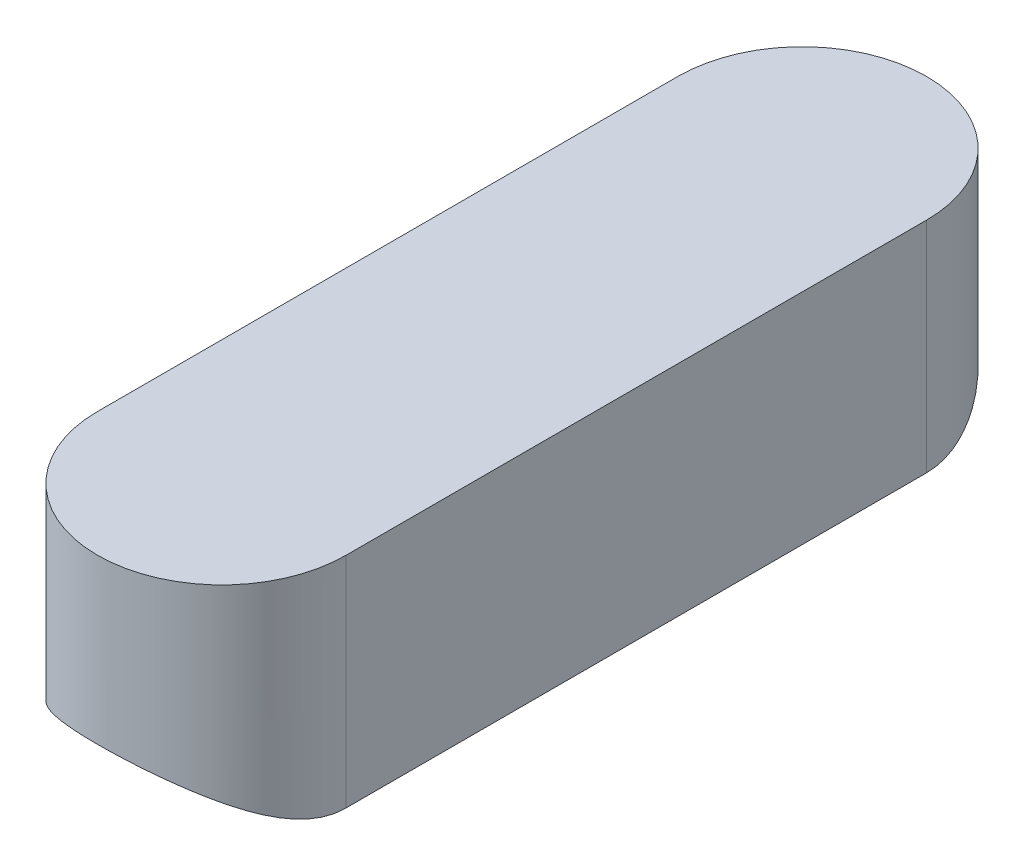
SolidWorks part; units mm, degrees
material "Polyetheretherketone (PEEK)"
ref_plane "Front Plane" through (0, 0, 0) normal (0, 0, 1) x (1, 0, 0)
ref_plane "Top Plane" through (0, 0, 0) normal (0, 1, 0) x (1, 0, 0)
ref_plane "Right Plane" through (0, 0, 0) normal (1, 0, 0) x (0, 0, -1)
sketch "Sketch1" plane through (0, 0, 0) normal (0, 0, 1) x (1, 0, 0)
  line L2 (3, 2.7208) -> (3, 8)
  line L3 (3, 8) -> (-3, 8)
  line L4 (-3, 2.7208) -> (-3, 8)
  line L5 (0, 0) -> (-3, 8) construction
  line L6 (3, 8) -> (0, 0) construction
  arc A0 (3, 2.7208) -> (-3, 2.7208) centre (0, 0) ccw
  dimension "D1" = 4.05
  dimension "D2" = 6
  dimension "D3" = 8
  dimension "D4" = 3
extrude "Boss-Extrude1" add sketch "Sketch1" along normal blind 20
sketch "Sketch2" plane through (0, 8, 0) normal (0, 1, 0) x (1, 0, 0)
  line L0 (0, 0) -> (0, -21.0822) construction
  line L1 (3, -20) -> (-3, -20) construction
  line L2 (-3, -3) -> (-3, -17)
  line L3 (3, -3) -> (3, -17)
  arc A0 (3, -3) -> (-3, -3) centre (0, -3) ccw
  arc A1 (-3, -17) -> (3, -17) centre (0, -17) ccw
  dimension "D1" = 6
  dimension "D2" = 6
extrude "Cut-Extrude2" cut sketch "Sketch2" against normal through all flip side to cut
